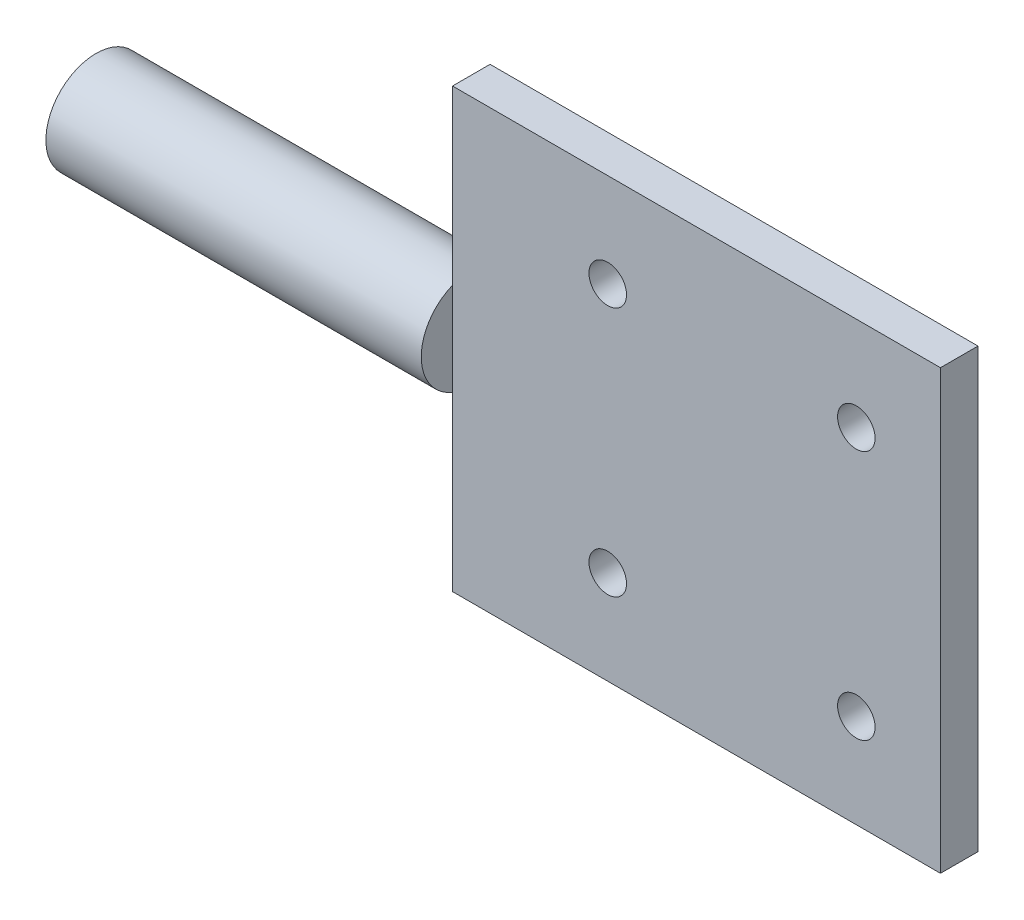
SolidWorks part; units mm, degrees
ref_plane "前视基准面" through (0, 0, 0) normal (0, 0, 1) x (1, 0, 0)
ref_plane "上视基准面" through (0, 0, 0) normal (0, 1, 0) x (1, 0, 0)
ref_plane "右视基准面" through (0, 0, 0) normal (1, 0, 0) x (0, 0, -1)
sketch "草图1" plane through (0, 0, 0) normal (0, 0, 1) x (1, 0, 0)
  line L1 (17, -17.5) -> (-17, -17.5)
  line L2 (17, -17.5) -> (17, 17.5)
  line L3 (17, 17.5) -> (-17, 17.5)
  line L4 (-17, -17.5) -> (-17, 17.5)
  line L5 (17, -17.5) -> (-17, 17.5) construction
  line L6 (17, 17.5) -> (-17, -17.5) construction
  point P0 (0, 0)
  dimension "D1" = 35
  dimension "D2" = 34
extrude "凸台-拉伸1" add sketch "草图1" along normal blind 3
sketch "草图2" plane through (0, 0, 3) normal (0, 0, 1) x (1, 0, 0)
  line L0 (-17, 0) -> (-28.5683, 0) construction
  line L1 (-17, 17.5) -> (-17, -17.5) construction
  line L2 (-17, -5) -> (-22, -5)
  line L3 (-17, 0) -> (-22, 0)
  line L4 (-17, -5) -> (-17, 5)
  line L5 (-17, 5) -> (-22, 5)
  line L6 (-22, -5) -> (-22, 5)
  line M3 (-17, 17.5) -> (-17, -17.5)
  dimension "D1" = 5
  dimension "D2" = 5
extrude "凸台-拉伸2" add sketch "草图2" against normal blind 3 contours L6 L3 L5 M3 | L6 L2 L3 M3
sketch "草图3" plane through (-22, 0, 0) normal (-1, 0, 0) x (0, 0, 1)
  line L0 (1.5, 5) -> (1.5, -5) construction
  line L1 (0, 5) -> (3, 5) construction
  line L2 (0, -5) -> (3, -5) construction
  line L3 (0, 0) -> (3, 0) construction
  line L4 (0, -5) -> (0, 5) construction
  line L5 (3, -5) -> (3, 5) construction
  circle A0 centre (1.5, 0) radius 10
  dimension "D1" = 20
sketch "草图7" plane through (0, 0, 3) normal (0, 0, 1) x (1, 0, 0)
  circle A0 centre (10.2752, 10) radius 1.5
  circle A1 centre (10.2752, -10) radius 1.5
  circle A2 centre (-9.5936, 10) radius 1.5
  circle A3 centre (-9.5936, -10) radius 1.5
  dimension "D1" = 10
  dimension "D2" = 10
  dimension "D3" = 10
  dimension "D5" = 3
  dimension "D4" = 10
extrude "切除-拉伸7" cut sketch "草图7" against normal blind 3
sketch "草图14" plane through (-22, 0, 0) normal (-1, 0, 0) x (0, 0, 1)
  circle A0 centre (1.5, 0) radius 4
extrude "凸台-拉伸6" add sketch "草图14" along normal blind 25
sketch "草图16" plane through (-22, 0, 0) normal (1, 0, 0) x (0, 0, -1)
  circle A0 centre (-1.5, 0) radius 4
extrude "凸台-拉伸7" add sketch "草图16" along normal up to surface (5 mm away) up to face at (-17, -11.25, 1.5)
sketch "草图17" plane through (-22, 0, 0) normal (-1, 0, 0) x (0, 0, 1)
  line L3 (3, 3.7081) -> (3, 5)
  line L4 (3, 5) -> (0, 5)
  line L5 (0, 5) -> (0, 3.7081)
  line L6 (3, 3.7081) -> (3, 5)
  line L7 (3, 5) -> (0, 5)
  line L8 (0, 5) -> (0, 3.7081)
  line L9 (0, -3.7081) -> (0, -5)
  line L10 (0, -5) -> (3, -5)
  line L11 (3, -5) -> (3, -3.7081)
  line L12 (0, -3.7081) -> (0, -5)
  line L13 (0, -5) -> (3, -5)
  line L14 (3, -5) -> (3, -3.7081)
  arc A1 (3, 3.7081) -> (0, 3.7081) centre (1.5, 0) ccw
  arc A2 (3, 3.7081) -> (0, 3.7081) centre (1.5, 0) ccw
  arc A3 (0, -3.7081) -> (3, -3.7081) centre (1.5, 0) ccw
  arc A4 (0, -3.7081) -> (3, -3.7081) centre (1.5, 0) ccw
  dimension "D1" = 0
  dimension "D2" = 0
extrude "切除-拉伸9" cut sketch "草图17" against normal up to surface (5 mm away) up to face at (-17, -11.25, 1.5)
sketch "草图18" plane through (-17, 0, 0) normal (-1, 0, 0) x (0, 0, 1)
  line L3 (3, -17.5) -> (3, -3.7081)
  line L4 (0, -3.7081) -> (0, -17.5)
  line L5 (0, -17.5) -> (3, -17.5)
  line L6 (3, -17.5) -> (3, -3.7081)
  line L7 (0, -3.7081) -> (0, -17.5)
  line L8 (0, -17.5) -> (3, -17.5)
  line L9 (0, 17.5) -> (0, 3.7081)
  line L10 (3, 3.7081) -> (3, 17.5)
  line L11 (3, 17.5) -> (0, 17.5)
  line L12 (0, 17.5) -> (0, 3.7081)
  line L13 (3, 3.7081) -> (3, 17.5)
  line L14 (3, 17.5) -> (0, 17.5)
  arc A1 (0, -3.7081) -> (3, -3.7081) centre (1.5, 0) ccw
  arc A2 (0, -3.7081) -> (3, -3.7081) centre (1.5, 0) ccw
  arc A3 (3, 3.7081) -> (0, 3.7081) centre (1.5, 0) ccw
  arc A4 (3, 3.7081) -> (0, 3.7081) centre (1.5, 0) ccw
  dimension "D1" = 0
  dimension "D2" = 0
extrude "凸台-拉伸8" add sketch "草图18" along normal blind 5
sketch "草图19" plane through (0, -17.5, 0) normal (0, -1, 0) x (1, 0, 0)
  line L1 (-22, 3) -> (-17, 3)
  line L2 (-22, 3) -> (-22, 5.5)
  line L3 (-22, 5.5) -> (-17, 5.5)
  line L4 (-17, 3) -> (-17, 5.5)
  line L5 (-22, 0) -> (-17, 0)
  line L6 (-22, 0) -> (-22, -2.5)
  line L7 (-22, -2.5) -> (-17, -2.5)
  line L8 (-17, 0) -> (-17, -2.5)
extrude "切除-拉伸10" cut sketch "草图19" against normal through all
sketch "草图20" plane through (-47, 0, 0) normal (-1, 0, 0) x (0, 0, 1)
  circle A1 centre (1.5, 0) radius 4
  circle A2 centre (1.5, 0) radius 4
  dimension "D1" = 0
extrude "凸台-拉伸9" add sketch "草图20" along normal blind 29.5
sketch "草图21" plane through (0, -17.5, 0) normal (0, -1, 0) x (1, 0, 0)
  line L1 (-22, -2.5) -> (-52, -2.5)
  line L2 (-22, -2.5) -> (-22, 7.8902)
  line L3 (-22, 7.8902) -> (-52, 7.8902)
  line L4 (-52, -2.5) -> (-52, 7.8902)
  line L5 (-52, -2.5) -> (-78.9803, -2.5)
  line L6 (-52, -2.5) -> (-52, 7.8902)
  line L7 (-52, 7.8902) -> (-78.9803, 7.8902)
  line L8 (-78.9803, -2.5) -> (-78.9803, 7.8902)
  dimension "D1" = 30
extrude "切除-拉伸11" cut sketch "草图21" against normal through all contours L8 L5 L4 L7
